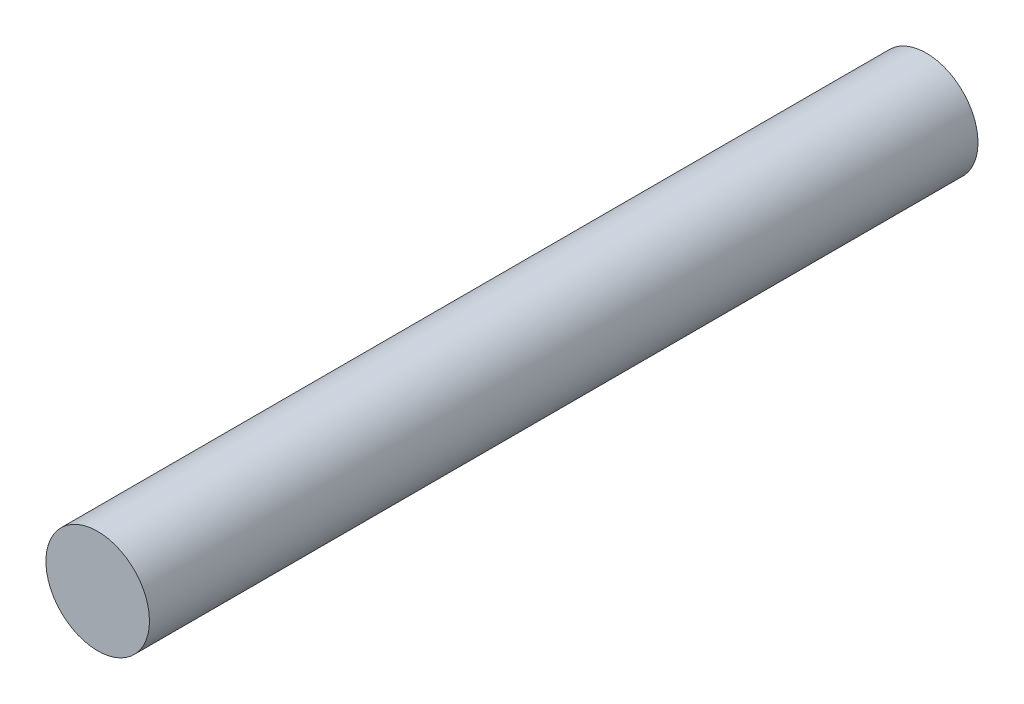
SolidWorks part; units mm, degrees
ref_plane "Front Plane" through (0, 0, 0) normal (0, 0, 1) x (1, 0, 0)
ref_plane "Top Plane" through (0, 0, 0) normal (0, 1, 0) x (1, 0, 0)
ref_plane "Right Plane" through (0, 0, 0) normal (1, 0, 0) x (0, 0, -1)
sketch "Sketch1" plane through (0, 0, 0) normal (0, 0, 1) x (1, 0, 0)
  circle A0 centre (0, 0) radius 1.5875
  dimension "D1" = 3.175
extrude "Boss-Extrude1" add sketch "Sketch1" along normal blind 25.4
equation "\"Input_Diameter\"= 0.125"
equation "\"Shaft_Length\"= 1"
equation "\"D1@Sketch1\"=\"Input_Diameter\""
equation "\"D1@Boss-Extrude1\"=\"Shaft_Length\""
